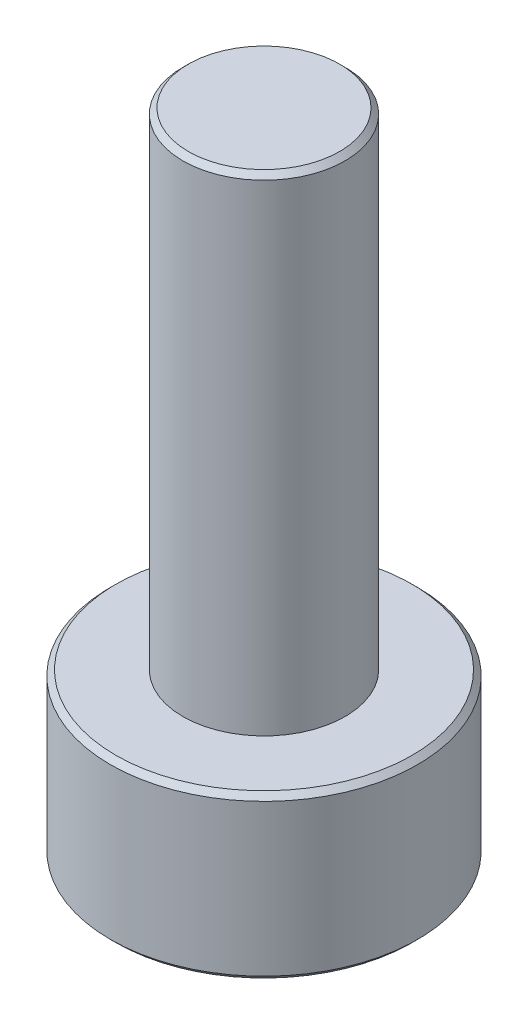
SolidWorks part; units mm, degrees
material "Q235"
ref_plane "前视基准面" through (0, 0, 0) normal (0, 0, 1) x (1, 0, 0)
ref_plane "上视基准面" through (0, 0, 0) normal (0, 1, 0) x (1, 0, 0)
ref_plane "右视基准面" through (0, 0, 0) normal (1, 0, 0) x (0, 0, -1)
sketch "草图1" plane through (0, 0, 0) normal (0, 1, 0) x (1, 0, 0)
  circle A0 centre (0, 0) radius 2.84
  dimension "D1" = 5.68
extrude "杯头部分" add sketch "草图1" along normal blind 3
sketch "草图2" plane through (0, 3, 0) normal (0, 1, 0) x (1, 0, 0)
  circle A0 centre (0, 0) radius 1.5
  dimension "D1" = 3
extrude "螺柱部分" add sketch "草图2" along normal blind 9
cosmetic thread "装饰螺纹线1" parameters "D2"=2.459
sketch "草图3" plane through (0, 0, 0) normal (0, -1, 0) x (1, 0, 0)
  line L1 (1.29, -0.7448) -> (1.29, 0.7448)
  line L2 (1.29, 0.7448) -> (0, 1.4896)
  line L3 (0, 1.4896) -> (-1.29, 0.7448)
  line L4 (-1.29, 0.7448) -> (-1.29, -0.7448)
  line L5 (-1.29, -0.7448) -> (0, -1.4896)
  line L6 (0, -1.4896) -> (1.29, -0.7448)
  circle A0 centre (0, 0) radius 1.29 construction
  dimension "D1" = 2.58
extrude "沉头内六角" cut sketch "草图3" against normal blind 1.3
chamfer "修饰性倒角" distance 0.1 angle 45 3 edges at (0, 12, 1.5) (0, 3, 2.84) (0, 0, 2.84)
